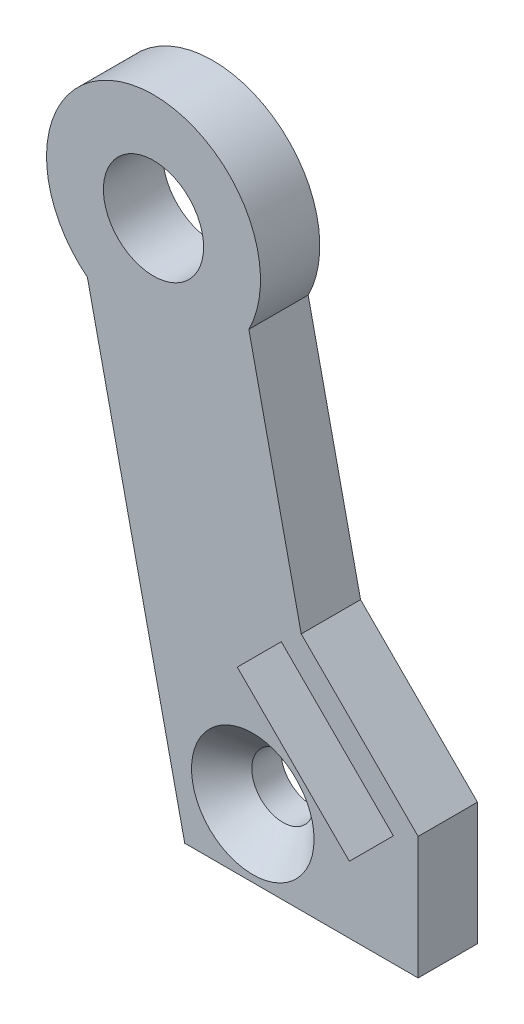
SolidWorks part; units mm, degrees
ref_plane "Front Plane" through (0, 0, 0) normal (0, 0, 1) x (1, 0, 0)
ref_plane "Top Plane" through (0, 0, 0) normal (0, 1, 0) x (1, 0, 0)
ref_plane "Right Plane" through (0, 0, 0) normal (1, 0, 0) x (0, 0, -1)
sketch "Sketch1" plane through (0, 0, 0) normal (0, 0, 1) x (1, 0, 0)
  line L0 (0, 12) -> (12, 0) construction
  line L1 (0, 0) -> (12, 0)
  line L2 (0, 0) -> (0, 12) construction
  line L3 (0, 12) -> (12, 12) construction
  line L4 (12, 0) -> (12, 12) construction
  line L5 (0, 0) -> (3.5, 0)
  line L6 (0, 0) -> (0, 3.5)
  line L7 (0, 3.5) -> (3.5, 3.5) construction
  line L8 (3.5, 0) -> (3.5, 3.5) construction
  line L9 (8.2662, 3.6278) -> (8.3192, 3.6808) construction
  line L10 (8.4645, 3.4295) -> (2.7015, 9.1924)
  line L11 (2.7015, 9.1924) -> (4.9643, 11.4551)
  line L12 (8.4645, 3.4295) -> (10.7272, 5.6922)
  line L13 (4.9643, 11.4551) -> (10.7272, 5.6922)
  line L14 (0, 0) -> (-5.7554, 26.1095)
  line L15 (-5.7554, 26.1095) -> (2.5454, 27.9392)
  line L16 (2.5454, 27.9392) -> (5.9896, 12.3143)
  line L17 (5.9896, 12.3143) -> (12, 6.3039)
  line L18 (12, 0) -> (8.5175, 3.4825)
  line L19 (12, 6.3039) -> (12, 0)
  line L20 (0, 0) -> (0, 40.9886) construction
  circle A0 centre (3.5, 3.5) radius 1.5
  circle A1 centre (-1.605, 27.0243) radius 2.575
  circle A3 centre (-1.605, 27.0243) radius 5.5
  point P16 (-0.3519, 26.3442)
  point P24 (-1.4262, 26.0813)
  point P26 (-2.0544, 28.6764)
  dimension "D5" = 3
  dimension "D6" = 5.15
  dimension "D7" = 11
  dimension "D1" = 12
  dimension "D2" = 12
  dimension "D3" = 3.5
  dimension "D4" = 3.5
  dimension "D8" = 45
  dimension "D9" = 6.3039
  dimension "D10" = 90
  dimension "D11" = 90
  dimension "D12" = 16
  dimension "D13" = 8.5
  dimension "D14" = 3.2
  dimension "D15" = 8.15
  dimension "D16" = 0.075
  dimension "D17" = 4.925
  dimension "D18" = 8.5
extrude "Boss-Extrude1" add sketch "Sketch1" along normal blind 3.05 contours L15 A3 A1 | L15 A3 A1 | A3 L14 L2 L10 L11 L13 L3 L17 L16 | L17 L3 L13 L12 L0 L4 | A0 L8 L1 L0 L2 L7 | A0 L7 L2 L1 L8
hole_wizard "CSK for M3 Flat Head Machine Screw1" positions "Sketch2" profile "Sketch3" countersink size "M3" standard "ANSI Metric" end condition through all
sketch "Sketch2" plane through (0, 0, 3.05) normal (0, 0, 1) x (1, 0, 0)
  point P0 (3.5, 3.5)
sketch "Sketch3" plane through (3.5, 3.5, 3.05) normal (1, 0, 0) x (0, -1, 0)
  line L0 (0, 0) -> (0, 3.05)
  line L1 (0, 3.05) -> (1.6, 3.05)
  line L2 (1.6, 3.05) -> (1.6, 1.55)
  line L3 (1.6, 1.55) -> (3.15, 0)
  line L5 (3.15, 0) -> (0, 0)
  line L6 (-1.6, 1.55) -> (-3.15, 0) construction
  line L11 (0, -6.35) -> (0, 107.95) construction
  dimension "Thru Hole Dia." = 3.2
  dimension "Thru Hole Depth" = 3.05
  dimension "Near C'Sink Dia." = 6.3
  dimension "Near C'Sink Angle" = 90
